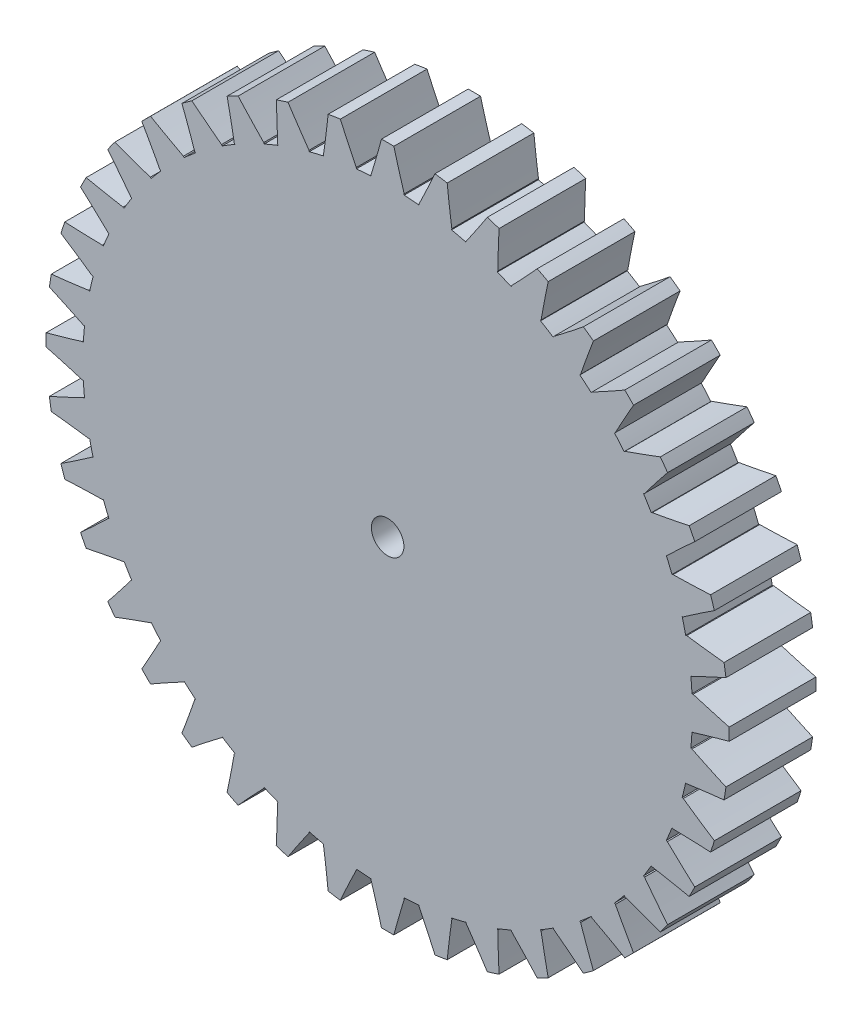
SolidWorks part; units mm, degrees
material "Aluminum Bronze"
ref_plane "Front Plane" through (0, 0, 0) normal (0, 0, 1) x (1, 0, 0)
ref_plane "Top Plane" through (0, 0, 0) normal (0, 1, 0) x (1, 0, 0)
ref_plane "Right Plane" through (0, 0, 0) normal (1, 0, 0) x (0, 0, -1)
sketch "Sketch2" plane through (0, 0, 0) normal (0, 0, 1) x (1, 0, 0)
  circle A0 centre (0, 0) radius 28.125
  dimension "D1" = 56.25
extrude "Boss-Extrude1" add sketch "Sketch2" along normal blind 8
sketch "Sketch3" plane through (0, 0, 8) normal (0, 0, 1) x (1, 0, 0)
  line L0 (0, 0) -> (0, 40) construction
  line L1 (0, 0) -> (0.9973, 30) construction
  line L2 (0, 0) -> (0.5711, 31.5191) construction
  line L3 (0, 0) -> (1.5287, 28.191)
  line L4 (0, 0) -> (-1.5287, 28.191)
  arc A0 (1.5287, 28.191) -> (0.5711, 31.5191) centre (92.5929, 56.1964) cw
  arc A1 (-1.5287, 28.191) -> (-0.5711, 31.5191) centre (-92.5929, 56.1964) ccw
  arc A2 (0.5711, 31.5191) -> (-0.5711, 31.5191) centre (0, 0) ccw
extrude "Boss-Extrude4" add sketch "Sketch3" against normal through all
pattern_circular "CirPattern1" count 40 over 360 about axis through (0, 0, 0) along (0, 0, 1) of "Boss-Extrude4"
sketch "Sketch4" plane through (0, 0, 8) normal (0, 0, 1) x (1, 0, 0)
  circle A0 centre (0, 0) radius 1.5
  dimension "D1" = 3
extrude "Cut-Extrude1" cut sketch "Sketch4" against normal through all
sketch "Sketch5" plane through (0, 0, 8) normal (0, 0, 1) x (1, 0, 0)
